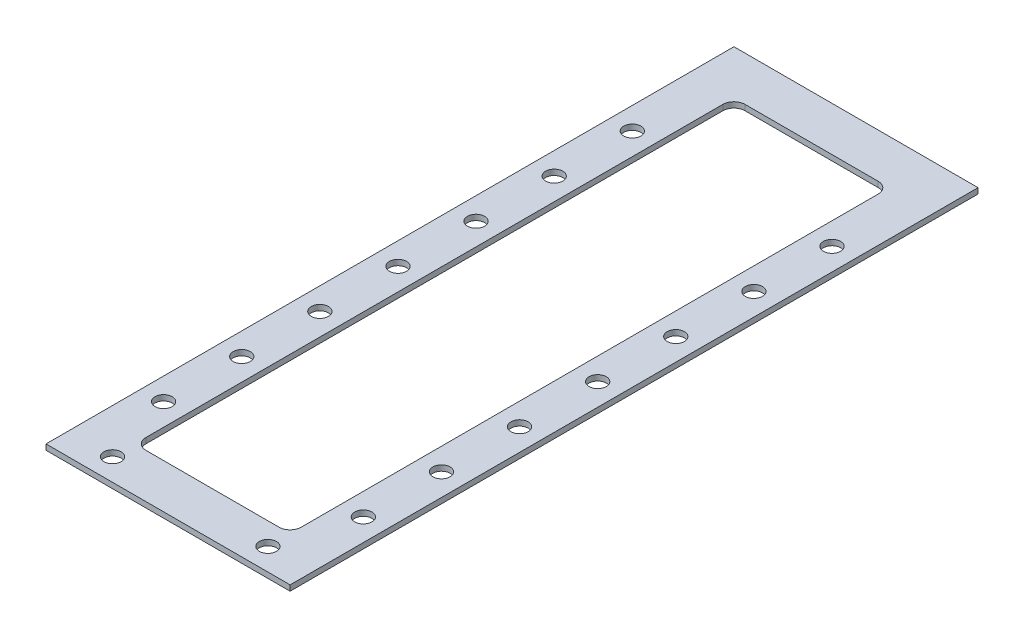
SolidWorks part; units mm, degrees
material "6061-T6 AL"
ref_plane "Front" through (0, 0, 0) normal (0, 0, 1) x (1, 0, 0)
ref_plane "Top" through (0, 0, 0) normal (0, 1, 0) x (1, 0, 0)
ref_plane "Right" through (0, 0, 0) normal (1, 0, 0) x (0, 0, -1)
sketch "Sketch1" plane through (0, 0, 0) normal (0, 1, 0) x (1, 0, 0)
  line L0 (0, 0) -> (69.85, 0)
  line L1 (0, 0) -> (0, 196.8246)
  line L2 (69.85, 0) -> (69.85, 196.8246)
  line L3 (0.0254, 196.85) -> (69.8246, 196.85)
  line L4 (12.7, 15.875) -> (12.7, 180.975)
  line L5 (15.875, 184.15) -> (53.975, 184.15)
  line L6 (57.15, 15.875) -> (57.15, 180.975)
  line L7 (15.875, 12.7) -> (53.975, 12.7)
  line L8 (12.7, 12.7) -> (12.7, 184.15) construction
  line L9 (12.7, 12.7) -> (57.15, 12.7) construction
  line L10 (57.15, 12.7) -> (57.15, 184.15) construction
  line L11 (12.7, 184.15) -> (57.15, 184.15) construction
  line L12 (0, 0) -> (0, 196.85) construction
  line L13 (0, 196.85) -> (69.85, 196.85) construction
  line L14 (69.85, 0) -> (69.85, 196.85) construction
  arc A0 (12.7, 15.875) -> (15.875, 12.7) centre (15.875, 15.875) ccw
  arc A1 (57.15, 15.875) -> (53.975, 12.7) centre (53.975, 15.875) cw
  arc A2 (53.975, 184.15) -> (57.15, 180.975) centre (53.975, 180.975) cw
  arc A3 (12.7, 180.975) -> (15.875, 184.15) centre (15.875, 180.975) cw
  arc A4 (0, 196.8246) -> (0.0254, 196.85) centre (0.0254, 196.8246) cw
  arc A5 (69.85, 196.8246) -> (69.8246, 196.85) centre (69.8246, 196.8246) ccw
  point P24 (0, 196.85)
  dimension "D4" = 3.175
  dimension "D5" = 0.0254
  dimension "D1" = 196.85
  dimension "D2" = 69.85
  dimension "D3" = 12.7
extrude "Boss-Extrude1" add sketch "Sketch1" along normal blind 1.5875
hole_wizard "#8 Clearance Hole1" positions "Sketch2" profile "Sketch3" hole size "#8" standard "ANSI Inch" end condition through all
sketch "Sketch2" plane through (0, 0, 0) normal (0, -1, 0) x (-1, 0, 0)
  line L0 (-34.925, 0) -> (-34.925, 12.7) construction
  line L1 (0, 0) -> (-69.85, 0) construction
  line L2 (-15.875, 12.7) -> (-53.975, 12.7) construction
  line L4 (-34.925, 6.35) -> (-57.15, 6.35) construction
  line L6 (-34.925, 6.35) -> (-12.7, 6.35) construction
  line L10 (-63.5, 27.305) -> (-6.35, 27.305) construction
  line L12 (-34.925, 12.7) -> (-34.925, 27.305) construction
  line L14 (-63.5, 49.657) -> (-6.35, 49.657) construction
  line L15 (-63.5, 72.009) -> (-6.35, 72.009) construction
  line L16 (-63.5, 94.361) -> (-6.35, 94.361) construction
  line L17 (-63.5, 116.713) -> (-6.35, 116.713) construction
  line L18 (-63.5, 139.065) -> (-6.35, 139.065) construction
  line L19 (-63.5, 27.305) -> (-63.5, 49.657) construction
  line L20 (-63.5, 161.417) -> (-6.35, 161.417) construction
  point P9 (-57.15, 6.35)
  point P13 (-12.7, 6.35)
  point P30 (-34.925, 27.305)
  point P37 (-63.5, 27.305)
  point P40 (-6.35, 27.305)
  point P61 (-63.5, 139.065)
  point P64 (-63.5, 116.713)
  point P67 (-63.5, 94.361)
  point P70 (-63.5, 72.009)
  point P74 (-6.35, 49.657)
  point P77 (-6.35, 72.009)
  point P80 (-6.35, 94.361)
  point P83 (-6.35, 116.713)
  point P86 (-6.35, 139.065)
  point P93 (-63.5, 49.657)
  point P98 (-63.5, 161.417)
  point P101 (-6.35, 161.417)
  dimension "D1" = 22.225
  dimension "D2" = 20.955
  dimension "D3" = 57.15
  dimension "D5" = 22.352
  dimension "D4" = 7
sketch "Sketch3" plane through (6.35, 0, -161.417) normal (1, 0, 0) x (0, 0, -1)
  line L0 (0, 0) -> (0, 1.5875)
  line L1 (0, 1.5875) -> (2.4574, 1.5875)
  line L2 (2.4574, 1.5875) -> (2.4574, 0)
  line L5 (2.4574, 0) -> (0, 0)
  line L11 (0, -6.35) -> (0, 107.95) construction
  dimension "Thru Hole Dia." = 4.9149
  dimension "Thru Hole Depth" = 1.5875
equation "\".0010.500in\"=0"
